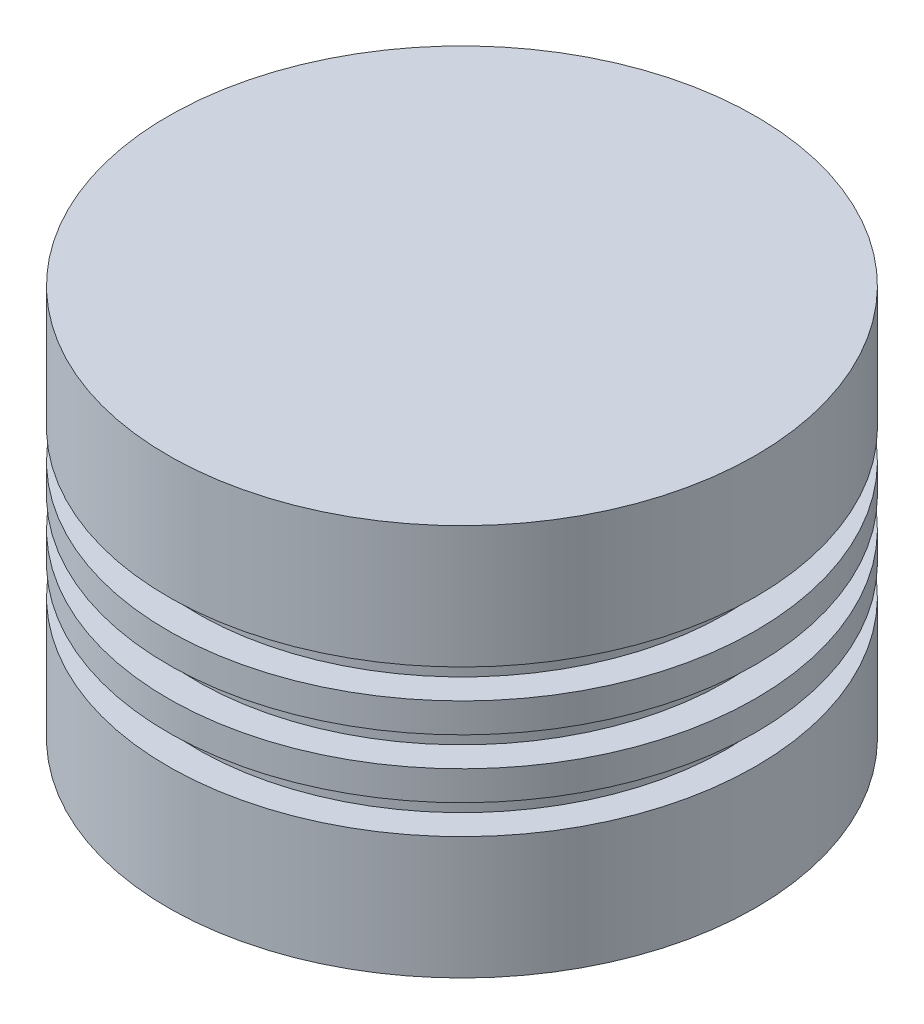
SolidWorks part; units mm, degrees
ref_plane "Front Plane" through (0, 0, 0) normal (0, 0, 1) x (1, 0, 0)
ref_plane "Top Plane" through (0, 0, 0) normal (0, 1, 0) x (1, 0, 0)
ref_plane "Right Plane" through (0, 0, 0) normal (1, 0, 0) x (0, 0, -1)
sketch "Sketch1" plane through (0, 0, 0) normal (0, 0, 1) x (1, 0, 0)
  line L0 (0, 0) -> (0, 100)
  line L1 (0, 100) -> (-75, 100)
  line L2 (-75, 100) -> (-75, 68.75)
  line L3 (-75, 68.75) -> (-67.5, 68.75)
  line L4 (-67.5, 68.75) -> (-67.5, 61.25)
  line L5 (-67.5, 61.25) -> (-75, 61.25)
  line L6 (-75, 61.25) -> (-75, 53.75)
  line L7 (-75, 53.75) -> (-67.5, 53.75)
  line L8 (-67.5, 53.75) -> (-67.5, 46.25)
  line L9 (-67.5, 46.25) -> (-75, 46.25)
  line L10 (-75, 46.25) -> (-75, 38.75)
  line L11 (-75, 38.75) -> (-67.5, 38.75)
  line L12 (-67.5, 38.75) -> (-67.5, 31.25)
  line L13 (-67.5, 31.25) -> (-75, 31.25)
  line L14 (-75, 31.25) -> (-75, 0)
  line L15 (-75, 0) -> (0, 0)
  line L16 (-67.5, 50) -> (0, 50) construction
  dimension "D1" = 7.5
  dimension "D2" = 7.5
  dimension "D3" = 100
  dimension "D4" = 75
revolve "Revolve1" add sketch "Sketch1" angle 360 about L0
sketch "Sketch2" plane through (0, 0, 0) normal (0, -1, 0) x (1, 0, 0)
  line L1 (-31.25, 31.25) -> (31.25, 31.25)
  line L2 (-31.25, 31.25) -> (-31.25, -31.25)
  line L3 (-31.25, -31.25) -> (31.25, -31.25)
  line L4 (31.25, 31.25) -> (31.25, -31.25)
  line L5 (-31.25, 31.25) -> (31.25, -31.25) construction
  line L6 (-31.25, -31.25) -> (31.25, 31.25) construction
  point P0 (0, 0)
  dimension "D1" = 62.5
extrude "Cut-Extrude1" cut sketch "Sketch2" against normal blind 50
sketch "Sketch3" plane through (31.25, 0, 0) normal (-1, 0, 0) x (0, 0, 1)
  line L0 (0, 0) -> (0, 50) construction
  line L1 (-31.25, 0) -> (31.25, 0) construction
  line L2 (-31.25, 50) -> (31.25, 50) construction
  circle A0 centre (0, 25) radius 10
  dimension "D1" = 20
extrude "Boss-Extrude1" add sketch "Sketch3" along normal up to next
fillet "Fillet1" radius 25 2 edges at (0, 50, -31.25) (0, 50, 31.25)
